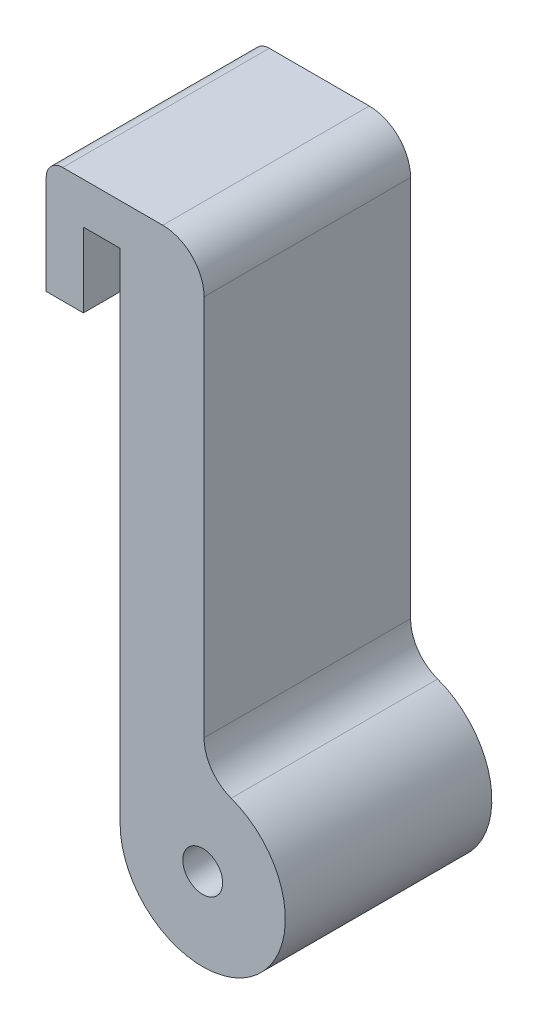
SolidWorks part; units mm, degrees
ref_plane "Front Plane" through (0, 0, 0) normal (0, 0, 1) x (1, 0, 0)
ref_plane "Top Plane" through (0, 0, 0) normal (0, 1, 0) x (1, 0, 0)
ref_plane "Right Plane" through (0, 0, 0) normal (1, 0, 0) x (0, 0, -1)
sketch "Sketch1" plane through (0, 0, 0) normal (0, 0, 1) x (1, 0, 0)
  line L0 (-20, 120.65) -> (-28.89, 120.65)
  line L2 (-33.89, 130.65) -> (-9.68, 130.65)
  line L4 (-20, 120.65) -> (-20, 0)
  line L5 (-28.89, 120.65) -> (-28.89, 102.65)
  line L6 (-28.89, 102.65) -> (-37.89, 102.65)
  line L7 (-37.89, 102.65) -> (-37.89, 126.65)
  line L8 (0.32, 28.1691) -> (0.32, 120.65)
  circle A0 centre (0, 0) radius 4.826
  arc A1 (6.88, 18.7794) -> (-20, 0) centre (0, 0) cw
  arc A2 (-9.68, 130.65) -> (0.32, 120.65) centre (-9.68, 120.65) cw
  arc A3 (0.32, 28.1691) -> (6.88, 18.7794) centre (10.32, 28.1691) ccw
  arc A4 (-37.89, 126.65) -> (-33.89, 130.65) centre (-33.89, 126.65) cw
  dimension "D1" = 9.652
  dimension "D2" = 20
  dimension "D9" = 10
  dimension "D10" = 4
  dimension "D3" = 10
  dimension "D4" = 8.89
  dimension "D5" = 9
  dimension "D6" = 20.32
  dimension "D7" = 120.65
  dimension "D8" = 18
extrude "Boss-Extrude1" add sketch "Sketch1" along normal blind 50
